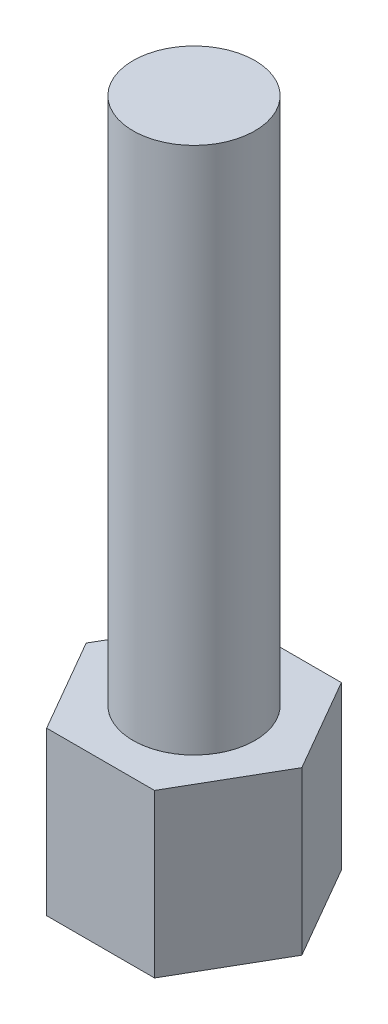
SolidWorks part; units mm, degrees
ref_plane "Front" through (0, 0, 0) normal (0, 0, 1) x (1, 0, 0)
ref_plane "Top" through (0, 0, 0) normal (0, 1, 0) x (1, 0, 0)
ref_plane "Right" through (0, 0, 0) normal (1, 0, 0) x (0, 0, -1)
sketch "草图1" plane through (0, 0, 0) normal (0, 1, 0) x (1, 0, 0)
  line L1 (-1.3279, 2.3) -> (-2.6558, 0)
  line L2 (-2.6558, 0) -> (-1.3279, -2.3)
  line L3 (-1.3279, -2.3) -> (1.3279, -2.3)
  line L4 (1.3279, -2.3) -> (2.6558, 0)
  line L5 (2.6558, 0) -> (1.3279, 2.3)
  line L6 (1.3279, 2.3) -> (-1.3279, 2.3)
  circle A0 centre (0, 0) radius 2.3 construction
  circle A1 centre (0, 0) radius 1.5 construction
  dimension "D2" = 3
  dimension "D1" = 4.6
extrude "凸台-拉伸1" add sketch "草图1" along normal blind 4
sketch "草图3" plane through (0, 4, 0) normal (0, 1, 0) x (1, 0, 0)
  circle A0 centre (0, 0) radius 1.5
  dimension "D1" = 3
extrude "凸台-拉伸2" add sketch "草图3" along normal blind 13
cosmetic thread "装饰螺纹线2" parameters "D2"=2
sketch "草图4" plane through (0, 0, 0) normal (0, -1, 0) x (1, 0, 0)
  circle A0 centre (0, 0) radius 1.5
  dimension "D1" = 3
extrude "切除-拉伸1" cut sketch "草图4" against normal up to surface (4 mm away) up to face at (0, 4, 1.5)
cosmetic thread "装饰螺纹线1" parameters "D2"=4
ref_plane "基准面1" through (0, 2, 0) normal (0, 1, 0) x (1, 0, 0)
